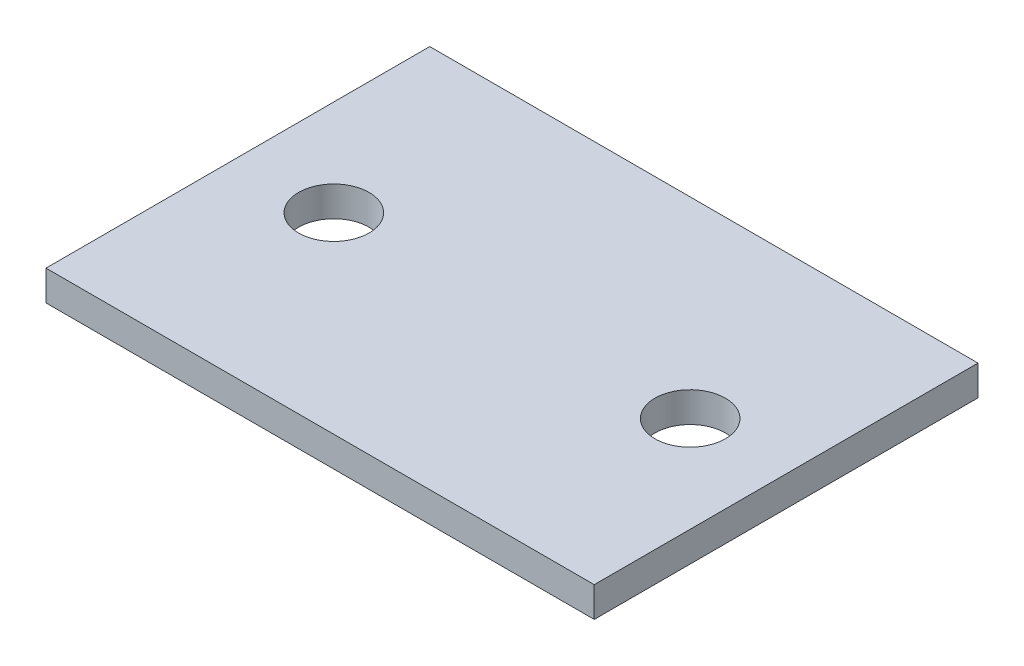
SolidWorks part; units mm, degrees
material "6061-T6 (SS)"
ref_plane "Front Plane" through (0, 0, 0) normal (0, 0, 1) x (1, 0, 0)
ref_plane "Top Plane" through (0, 0, 0) normal (0, 1, 0) x (1, 0, 0)
ref_plane "Right Plane" through (0, 0, 0) normal (1, 0, 0) x (0, 0, -1)
sketch "Sketch2" plane through (0, 0, 0) normal (0, 1, 0) x (1, 0, 0)
  line L0 (0, 0) -> (0, 50000) construction
  line L1 (0, 0) -> (50000, 0) construction
  line L3 (-25.4, 17.78) -> (25.4, 17.78)
  line L4 (-25.4, 17.78) -> (-25.4, -17.78)
  line L5 (-25.4, -17.78) -> (25.4, -17.78)
  line L6 (25.4, 17.78) -> (25.4, -17.78)
  circle A0 centre (-16.51, 0) radius 3.2639
  circle A1 centre (16.51, 0) radius 3.2639
  dimension "D5" = 6.5278
  dimension "D6" = 16.51
  dimension "D1" = 50.8
  dimension "D2" = 35.56
  dimension "D3" = 17.78
  dimension "D4" = 25.4
extrude "Boss-Extrude1" add sketch "Sketch2" along normal blind 2.794
